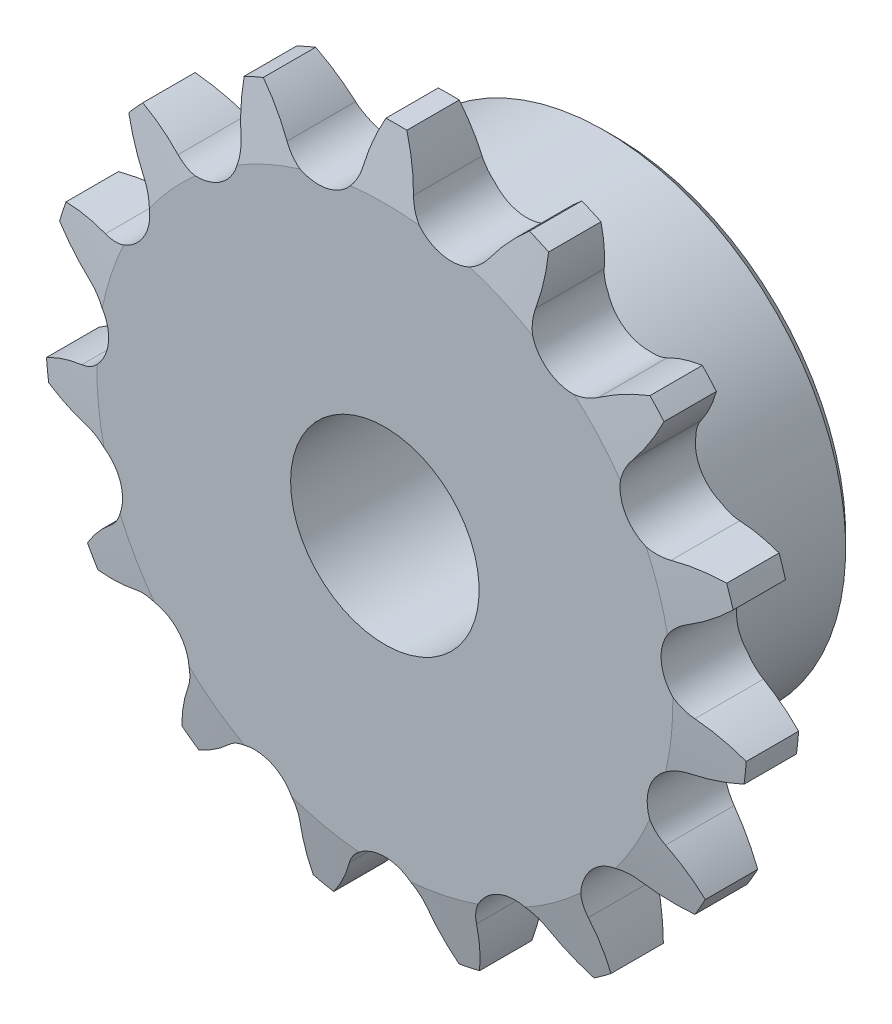
SolidWorks part; units mm, degrees
material "SUS304"
ref_plane "Front Plane" through (0, 0, 0) normal (0, 0, 1) x (1, 0, 0)
ref_plane "Top Plane" through (0, 0, 0) normal (0, 1, 0) x (1, 0, 0)
ref_plane "Right Plane" through (0, 0, 0) normal (1, 0, 0) x (0, 0, -1)
sketch "Sketch1" plane through (0, 0, 0) normal (1, 0, 0) x (0, 0, -1)
  line L0 (27.3653, 0) -> (0, 0) construction
  line L1 (0, 9) -> (22, 9)
  line L2 (22, 9) -> (22, 23)
  line L3 (22, 23) -> (7.2, 23)
  line L4 (7.2, 23) -> (7.2, 27.5)
  line L5 (6.1, 33.5) -> (1.1, 33.5)
  line L6 (0, 27.5) -> (0, 9)
  line L7 (6.1, 33.5) -> (7.2, 27.5)
  line L8 (3.6, 58.9526) -> (3.6, 63.7269) construction
  line L9 (1.1, 33.5) -> (0, 27.5)
  dimension "D1" = 7.2
  dimension "D2" = 5
  dimension "D3" = 18
  dimension "D4" = 67
  dimension "D5" = 6
  dimension "D6" = 46
  dimension "D7" = 22
revolve "Revolve1" add sketch "Sketch1" angle 360 about L0
chamfer "Chamfer1" distance 1 angle 45 1 edges at (-23, 0, -22)
sketch "Sketch2" plane through (0, 0, 0) normal (0, 0, 1) x (1, 0, 0)
  line L0 (0, 0) -> (0, 48.4341) construction
  line L1 (0, 0) -> (6.3496, 29.8726) construction
  circle A0 centre (0, 0) radius 30.54 construction
  circle A1 centre (6.3496, 29.8726) radius 4 construction
  arc A2 (2.4103, 29.1786) -> (9.6661, 27.6363) centre (6.3496, 29.8726) ccw
  circle A3 centre (17.951, 24.7074) radius 4 construction
  circle A4 centre (26.4484, 15.27) radius 4 construction
  circle A5 centre (30.3727, 3.1923) radius 4 construction
  circle A6 centre (29.0453, -9.4374) radius 4 construction
  circle A7 centre (22.6956, -20.4352) radius 4 construction
  circle A8 centre (12.4217, -27.8997) radius 4 construction
  circle A9 centre (0, -30.54) radius 4 construction
  circle A10 centre (-12.4217, -27.8997) radius 4 construction
  circle A11 centre (-22.6956, -20.4352) radius 4 construction
  circle A12 centre (-29.0453, -9.4374) radius 4 construction
  circle A13 centre (-30.3727, 3.1923) radius 4 construction
  circle A14 centre (-26.4484, 15.27) radius 4 construction
  circle A15 centre (-17.951, 24.7074) radius 4 construction
  circle A16 centre (-6.3496, 29.8726) radius 4 construction
  circle A21 centre (0, 0) radius 33.5 construction
  arc A22 (0, 33.5) -> (13.7137, 30.5644) centre (0, 0) ccw construction
  arc A23 (1, 33.4851) -> (2.4103, 29.1786) centre (-13.347, 26.4025) cw
  arc A24 (12.7061, 30.9969) -> (9.6661, 27.6363) centre (22.932, 18.6912) ccw
  arc A25 (12.7061, 30.9969) -> (1, 33.4851) centre (0, 0) ccw
  dimension "D1" = 61.08
  dimension "D2" = 12
  dimension "D3" = 8
  dimension "D5" = 16
  dimension "D6" = 8
  dimension "D4" = 2
extrude "Cut-Extrude1" cut sketch "Sketch2" against normal blind 10
pattern_circular "CirPattern1" count 15 over 360 about axis through (0, 0, 0) along (0, 0, 1) of "Cut-Extrude1"
equation "\"Mass Kg\"= \"SW-Mass\""
